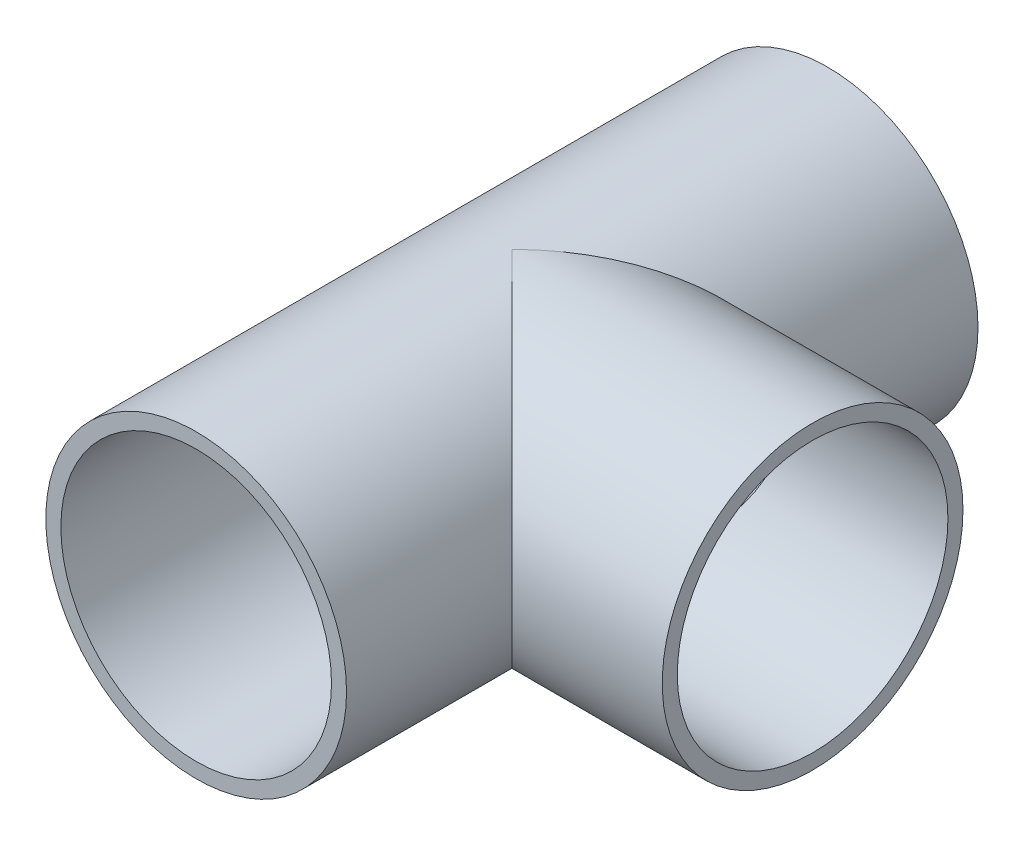
SolidWorks part; units mm, degrees
ref_plane "Front Plane" through (0, 0, 0) normal (0, 0, 1) x (1, 0, 0)
ref_plane "Top Plane" through (0, 0, 0) normal (0, 1, 0) x (1, 0, 0)
ref_plane "Right Plane" through (0, 0, 0) normal (1, 0, 0) x (0, 0, -1)
sketch "Sketch2" plane through (0, 0, 0) normal (0, 0, 1) x (1, 0, 0)
  circle A0 centre (0, 0) radius 12.7
  circle A1 centre (0, 0) radius 11.43
  dimension "D1" = 25.4
  dimension "D2" = 22.86
extrude "Boss-Extrude1" add sketch "Sketch2" along normal blind 53.34
ref_plane "Plane1" through (12.7, 0, 0) normal (1, 0, 0) x (0, 0, -1)
sketch "Sketch3" plane through (12.7, 0, 0) normal (1, 0, 0) x (0, 0, -1)
  line L0 (-53.34, 12.7) -> (-53.34, -12.7) construction
  line L2 (0, 0) -> (-26.67, 0)
  circle A0 centre (-26.67, 0) radius 11.43
  circle A1 centre (-26.67, 0) radius 12.7
  dimension "D2" = 22.86
  dimension "D4" = 25.4
  dimension "D1" = 26.67
  dimension "D3" = 0
extrude "Boss-Extrude2" add sketch "Sketch3" against normal blind 12.7
sketch "Sketch4" plane through (12.7, 0, 0) normal (1, 0, 0) x (0, 0, -1)
  circle A0 centre (-26.67, 0) radius 12.7
  circle A1 centre (-26.67, 0) radius 11.43
extrude "Boss-Extrude3" add sketch "Sketch4" along normal blind 12.7
sketch "Sketch5" plane through (25.4, 0, 0) normal (1, 0, 0) x (0, 0, -1)
  circle A0 centre (-26.67, 0) radius 11.43
extrude "Cut-Extrude1" cut sketch "Sketch5" against normal blind 25.4
sketch "Sketch6" plane through (0, 0, 0) normal (0, 0, -1) x (-1, 0, 0)
  circle A0 centre (0, 0) radius 11.43
extrude "Cut-Extrude2" cut sketch "Sketch6" against normal through all
